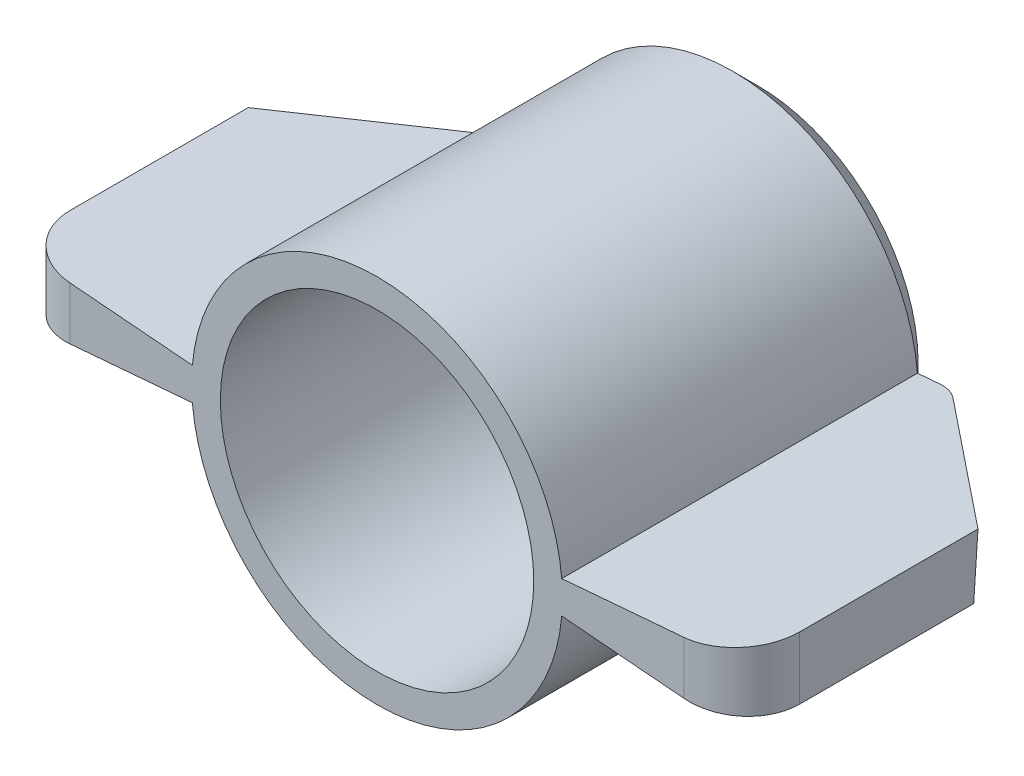
SolidWorks part; units mm, degrees
material "1023 Karbon Çeliği Levha (SS)"
ref_plane "Ön Düzlem" through (0, 0, 0) normal (0, 0, 1) x (1, 0, 0)
ref_plane "Üst Düzlem" through (0, 0, 0) normal (0, 1, 0) x (1, 0, 0)
ref_plane "Sağ Düzlem" through (0, 0, 0) normal (1, 0, 0) x (0, 0, -1)
sketch "Çizim1" plane through (0, 0, 0) normal (0, 0, 1) x (1, 0, 0)
  circle A0 centre (0, 0) radius 5.04
extrude "Yükseklik-Ekstrüzyon1" add sketch "Çizim1" along normal blind 10.35
chamfer "Pah1" distance 0.68 angle 45 1 edges at (5.04, 0, 0)
sketch "Çizim2" plane through (0, 0, 10.35) normal (0, 0, 1) x (1, 0, 0)
  circle A0 centre (0, 0) radius 4.26
extrude "Kes-Ekstrüzyon1" cut sketch "Çizim2" against normal blind 10.35
sketch "Çizim3" plane through (0, 0, 10.35) normal (0, 0, 1) x (1, 0, 0)
  line L0 (5.01, 0.44) -> (9.92, 0.85)
  line L1 (-5.01, 0) -> (-5.01, 0.44)
  line L2 (9.92, 0) -> (9.92, 0.85)
  line L3 (9.92, 0) -> (9.92, -0.85)
  line L4 (-9.92, 0) -> (-9.92, 0.85)
  line L5 (-9.92, 0) -> (-9.92, -0.85)
  line L6 (-5.04, 0) -> (-5.01, 0)
  line L7 (-5.01, 0) -> (-5.01, -0.44)
  line L8 (5.01, -0.44) -> (9.92, -0.85)
  line L9 (5.01, 0) -> (5.01, 0.44)
  line L10 (5.01, 0) -> (5.01, -0.44)
  line L11 (-9.92, 0.85) -> (-5.01, 0.44)
  line L12 (-5.01, -0.44) -> (-9.92, -0.85)
  circle A0 centre (0, 0) radius 5.04 construction
extrude "Yükseklik-Ekstrüzyon2" add sketch "Çizim3" against normal blind 9.67 contours L7 L12 L5 L4 L11 L1 | L2 L0 L9 L10 L8 L3
sketch "Çizim4" plane through (0.0018, -0.0215, 0) normal (0.0832, -0.9965, 0) x (-0.9965, -0.0832, 0)
  line L0 (9.9563, -10.35) -> (9.9563, -4.05)
  line L1 (9.9563, -0.68) -> (9.9563, -10.35) construction
  line L2 (5.04, -0.68) -> (5.88, -0.68)
  line L4 (5.04, -0.68) -> (9.9563, -0.68) construction
  line L5 (5.88, -0.68) -> (9.9563, -4.05)
  line L6 (9.9563, -0.68) -> (9.9563, -4.05)
  line L7 (9.9563, -0.68) -> (5.88, -0.68)
  line M3 (9.9563, -0.68) -> (5.04, -0.68)
  line M6 (9.9563, -10.35) -> (9.9563, -0.68)
extrude "Kes-Ekstrüzyon2" cut sketch "Çizim4" against normal through all both and the other way through all contours L5 M3 M6
sketch "Çizim5" plane through (-0.0018, -0.0215, 0) normal (-0.0832, -0.9965, 0) x (-0.9965, 0.0832, 0)
  line L0 (-9.9563, -10.35) -> (-9.9563, -4.05)
  line L1 (-9.9563, -0.68) -> (-9.9563, -10.35) construction
  line L2 (-5.04, -0.68) -> (-5.88, -0.68)
  line L3 (-5.04, -0.68) -> (-9.9563, -0.68) construction
  line L4 (-5.88, -0.68) -> (-9.9563, -4.05)
  line L5 (-9.9563, -0.68) -> (-9.9563, -4.05)
  line L6 (-9.9563, -0.68) -> (-5.88, -0.68)
  line M3 (-5.04, -0.68) -> (-9.9563, -0.68)
  line M4 (-9.9563, -0.68) -> (-9.9563, -10.35)
extrude "Kes-Ekstrüzyon3" cut sketch "Çizim5" against normal through all both and the other way through all contours L4 M3 M4
fillet "Radyus1" radius 0.84 1 edges at (5.9007, 0.0036, 0.68)
fillet "Radyus4" radius 0.84 1 edges at (-5.9007, 0.0036, 0.68)
fillet "Radyus5" radius 1.57 1 edges at (-9.92, 0, 10.35)
fillet "Radyus6" radius 1.57 1 edges at (9.92, 0, 10.35)
